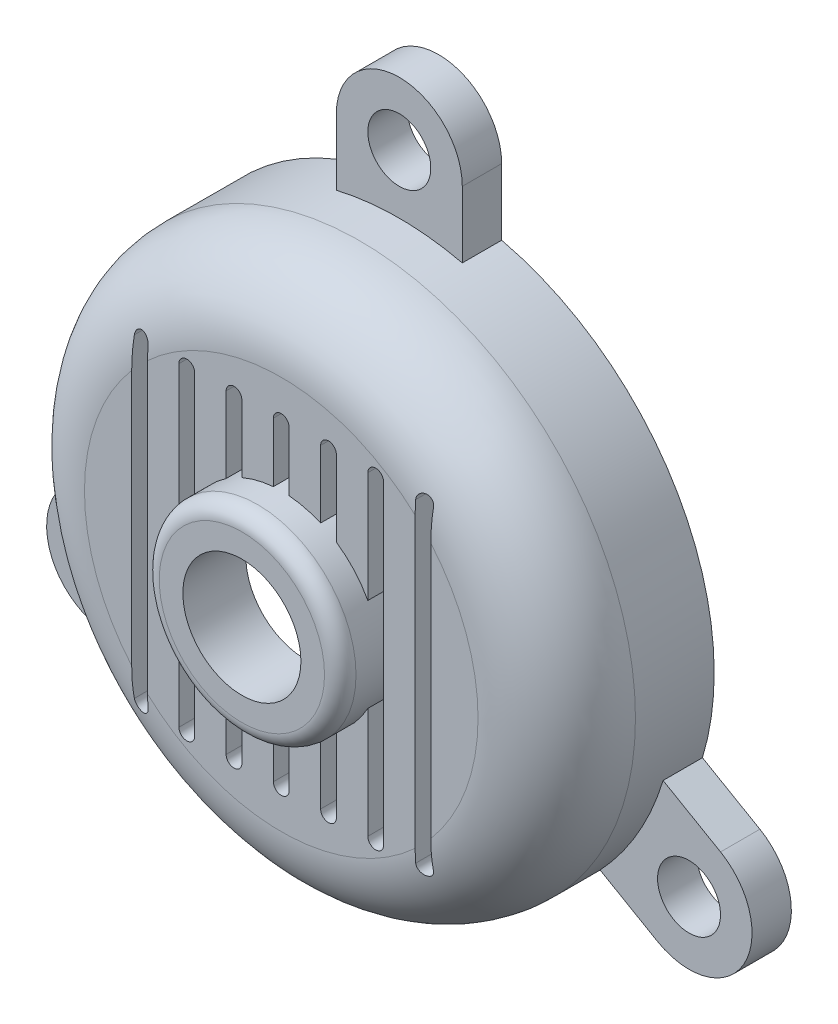
SolidWorks part; units mm, degrees
ref_plane "Front Plane" through (0, 0, 0) normal (0, 0, 1) x (1, 0, 0)
ref_plane "Top Plane" through (0, 0, 0) normal (0, 1, 0) x (1, 0, 0)
ref_plane "Right Plane" through (0, 0, 0) normal (1, 0, 0) x (0, 0, -1)
sketch "Sketch1" plane through (0, 0, 0) normal (0, 0, 1) x (1, 0, 0)
  circle A0 centre (0, 0) radius 350
extrude "Boss-Extrude1" add sketch "Sketch1" against normal blind 200
shell "Shell4" thickness 30
sketch "Sketch2" plane through (0, 0, -200) normal (0, 0, -1) x (-1, 0, 0)
  line L0 (0, -431.3347) -> (0, 472.5921) construction
  line L1 (-80, 425) -> (-80, 340.7345)
  line L2 (80, 425) -> (80, 340.7345)
  circle A0 centre (0, 0) radius 425 construction
  circle A2 centre (0, 425) radius 40
  arc A3 (80, 425) -> (-80, 425) centre (0, 425) ccw
  circle A4 centre (0, 0) radius 350 construction
  circle M4 centre (0, 0) radius 350
extrude "Boss-Extrude2" add sketch "Sketch2" against normal blind 50 contours L2 A3 L1 A2 M4
pattern_circular "CirPattern1" count 3 over 360 about axis through (0, 0, 0) along (0, 0, 1) of "Boss-Extrude2"
fillet "Fillet1" radius 100 1 edges at (350, 0, 0)
sketch "Sketch5" plane through (0, 0, 0) normal (0, 0, 1) x (1, 0, 0)
  line L0 (0, 1028.7767) -> (0, -1028.7767) construction
  line L1 (0, -200) -> (0, 200) construction
  line L2 (60, -200) -> (60, 200) construction
  line L3 (-10, -200) -> (-10, 200)
  line L4 (10, -200) -> (10, 200)
  line L5 (50, -200) -> (50, 200)
  line L6 (70, -200) -> (70, 200)
  line L7 (120, -200) -> (120, 200) construction
  line L8 (110, -200) -> (110, 200)
  line L9 (130, -200) -> (130, 200)
  line L10 (180, -200) -> (180, 200) construction
  line L11 (170, -200) -> (170, 200)
  line L12 (190, -200) -> (190, 200)
  line L13 (-60, -200) -> (-60, 200) construction
  line L14 (-70, -200) -> (-70, 200)
  line L15 (-50, -200) -> (-50, 200)
  line L16 (-120, -200) -> (-120, 200) construction
  line L17 (-130, -200) -> (-130, 200)
  line L18 (-110, -200) -> (-110, 200)
  line L19 (-180, -200) -> (-180, 200) construction
  line L20 (-190, -200) -> (-190, 200)
  line L21 (-170, -200) -> (-170, 200)
  arc A0 (-10, -200) -> (10, -200) centre (0, -200) ccw
  arc A1 (10, 200) -> (-10, 200) centre (0, 200) ccw
  arc A2 (50, -200) -> (70, -200) centre (60, -200) ccw
  arc A3 (70, 200) -> (50, 200) centre (60, 200) ccw
  arc A4 (110, -200) -> (130, -200) centre (120, -200) ccw
  arc A5 (130, 200) -> (110, 200) centre (120, 200) ccw
  arc A6 (170, -200) -> (190, -200) centre (180, -200) ccw
  arc A7 (190, 200) -> (170, 200) centre (180, 200) ccw
  arc A8 (-70, -200) -> (-50, -200) centre (-60, -200) ccw
  arc A9 (-50, 200) -> (-70, 200) centre (-60, 200) ccw
  arc A10 (-130, -200) -> (-110, -200) centre (-120, -200) ccw
  arc A11 (-110, 200) -> (-130, 200) centre (-120, 200) ccw
  arc A12 (-190, -200) -> (-170, -200) centre (-180, -200) ccw
  arc A13 (-170, 200) -> (-190, 200) centre (-180, 200) ccw
  point P4 (0, 0)
  point P7 (60, 0)
  point P12 (0, 0)
  point P21 (120, 0)
  point P28 (180, 0)
  point P34 (-60, 0)
  point P36 (-60, 0)
  point P42 (-120, 0)
  point P44 (-120, 0)
  point P50 (-180, 0)
  point P52 (-180, 0)
  dimension "D1" = 4
  dimension "D2" = 4
extrude "Cut-Extrude2" cut sketch "Sketch5" against normal blind 50
sketch "Sketch3" plane through (0, 0, 0) normal (0, 0, 1) x (1, 0, 0)
  circle A0 centre (0, 0) radius 75
  circle A1 centre (0, 0) radius 125
extrude "Boss-Extrude3" add sketch "Sketch3" along normal blind 80 from surface at -30 starting at face at (-180, 0, -30)
fillet "Fillet2" radius 20 1 edges at (125, 0, 50)
sketch "Sketch4" plane through (0, 0, 0) normal (0, 0, 1) x (1, 0, 0)
  circle A0 centre (0, 0) radius 75
extrude "Cut-Extrude1" cut sketch "Sketch4" against normal blind 50
